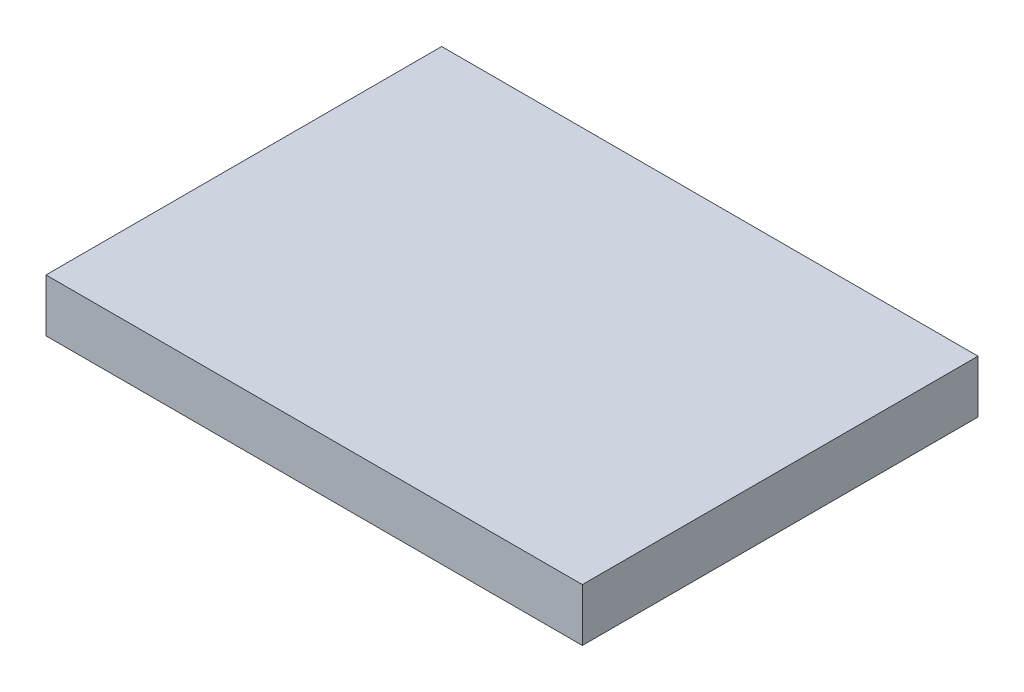
SolidWorks part; units mm, degrees
ref_plane "Front Plane" through (0, 0, 0) normal (0, 0, 1) x (1, 0, 0)
ref_plane "Top Plane" through (0, 0, 0) normal (0, 1, 0) x (1, 0, 0)
ref_plane "Right Plane" through (0, 0, 0) normal (1, 0, 0) x (0, 0, -1)
sketch "Sketch1" plane through (0, 0, 0) normal (0, 1, 0) x (1, 0, 0)
  line L1 (-30.5, -22.5) -> (30.5, -22.5)
  line L2 (-30.5, -22.5) -> (-30.5, 22.5)
  line L3 (-30.5, 22.5) -> (30.5, 22.5)
  line L4 (30.5, -22.5) -> (30.5, 22.5)
  line L5 (-30.5, -22.5) -> (30.5, 22.5) construction
  line L6 (-30.5, 22.5) -> (30.5, -22.5) construction
  point P0 (0, 0)
  dimension "D1" = 45
  dimension "D2" = 61
extrude "Boss-Extrude1" add sketch "Sketch1" along normal blind 6
